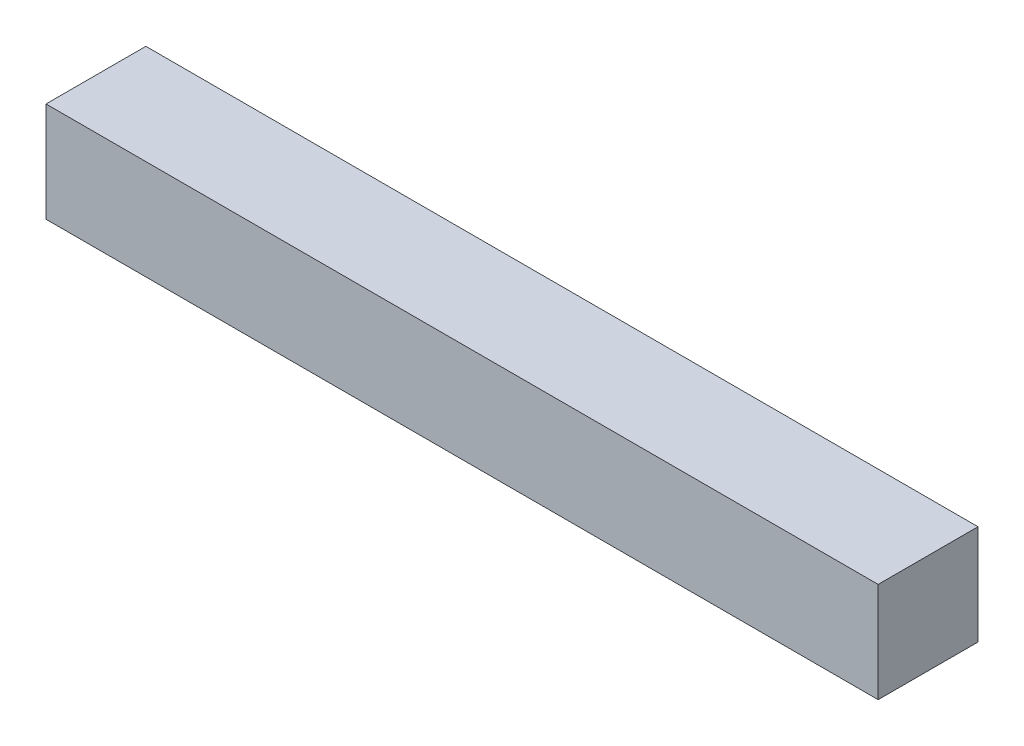
SolidWorks part; units mm, degrees
ref_plane "Front Plane" through (0, 0, 0) normal (0, 0, 1) x (1, 0, 0)
ref_plane "Top Plane" through (0, 0, 0) normal (0, 1, 0) x (1, 0, 0)
ref_plane "Right Plane" through (0, 0, 0) normal (1, 0, 0) x (0, 0, -1)
sketch "Sketch1" plane through (0, 0, 0) normal (0, 1, 0) x (1, 0, 0)
  line L1 (-25, -3) -> (25, -3)
  line L2 (-25, -3) -> (-25, 3)
  line L3 (-25, 3) -> (25, 3)
  line L4 (25, -3) -> (25, 3)
  line L5 (-25, -3) -> (25, 3) construction
  line L6 (-25, 3) -> (25, -3) construction
  point P0 (0, 0)
  dimension "D1" = 6
  dimension "D2" = 50
extrude "Boss-Extrude1" add sketch "Sketch1" along normal blind 6
